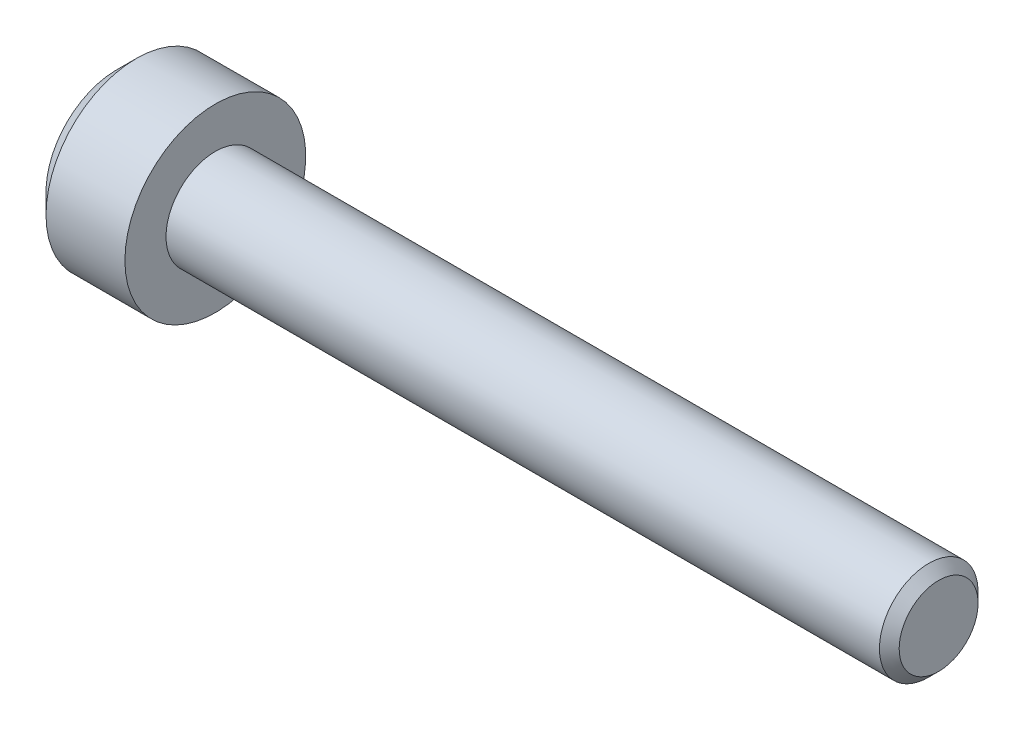
SolidWorks part; units mm, degrees
ref_plane "前视基准面" through (0, 0, 0) normal (0, 0, 1) x (1, 0, 0)
ref_plane "上视基准面" through (0, 0, 0) normal (0, 1, 0) x (1, 0, 0)
ref_plane "右视基准面" through (0, 0, 0) normal (1, 0, 0) x (0, 0, -1)
sketch "草图1" plane through (0, 0, 0) normal (0, 0, 1) x (1, 0, 0)
  line L0 (0, 0) -> (0, 1.5)
  line L1 (0, 1.5) -> (-22, 1.5)
  line L2 (-22, 1.5) -> (-22, 2.75)
  line L3 (-22, 2.75) -> (-25, 2.75)
  line L4 (-25, 2.75) -> (-25, 0)
  line L5 (-25, 0) -> (0, 0)
  line L6 (0, 0) -> (4.7488, 0) construction
  dimension "D1" = 3
  dimension "D2" = 22
  dimension "D3" = 3
  dimension "D4" = 5.5
revolve "旋转1" add sketch "草图1" angle 360 about L6
cosmetic thread "装饰螺纹线1" parameters "D1"=22, "D2"=2.58
chamfer "倒角1" distance 0.3 angle 45 1 edges at (0, 0, 1.5)
sketch "草图2" plane through (-25, 0, 0) normal (-1, 0, 0) x (0, 0, 1)
  line L1 (0, 1.4434) -> (-1.25, 0.7217)
  line L2 (-1.25, 0.7217) -> (-1.25, -0.7217)
  line L3 (-1.25, -0.7217) -> (0, -1.4434)
  line L4 (0, -1.4434) -> (1.25, -0.7217)
  line L5 (1.25, -0.7217) -> (1.25, 0.7217)
  line L6 (1.25, 0.7217) -> (0, 1.4434)
  circle A0 centre (0, 0) radius 1.25 construction
  dimension "D1" = 2.5
extrude "切除-拉伸1" cut sketch "草图2" against normal blind 1.5
chamfer "倒角2" distance 0.6 angle 45 1 edges at (-25, 0, 2.75)
sketch "草图4" plane through (-23.5, 0, 0) normal (-1, 0, 0) x (0, 0, 1)
  line L1 (0, -1.4434) -> (1.25, -0.7217)
  line L2 (1.25, -0.7217) -> (1.25, 0.7217)
  line L3 (1.25, 0.7217) -> (0, 1.4434)
  line L4 (0, 1.4434) -> (-1.25, 0.7217)
  line L5 (-1.25, 0.7217) -> (-1.25, -0.7217)
  line L6 (1.25, 0.7217) -> (0, 1.4434)
  line L7 (0, 1.4434) -> (-1.25, 0.7217)
  line L8 (-1.25, 0.7217) -> (-1.25, -0.7217)
  line L9 (-1.25, -0.7217) -> (0, -1.4434)
  line L10 (0, -1.4434) -> (1.25, -0.7217)
  line L11 (1.25, -0.7217) -> (1.25, 0.7217)
  line L12 (1.25, 0.7217) -> (0, 1.4434) construction
  line L13 (0, 1.4434) -> (-1.25, 0.7217) construction
  line L14 (-1.25, 0.7217) -> (-1.25, -0.7217) construction
  line L15 (-1.25, -0.7217) -> (0, -1.4434) construction
  line L16 (0, -1.4434) -> (1.25, -0.7217) construction
  line L17 (1.25, -0.7217) -> (1.25, 0.7217) construction
  line L18 (-1.25, -0.7217) -> (0, -1.4434)
  circle A0 centre (0, 0) radius 1.25 construction
  dimension "D1" = 0
extrude "切除-拉伸2" cut sketch "草图4" against normal through all draft 59
